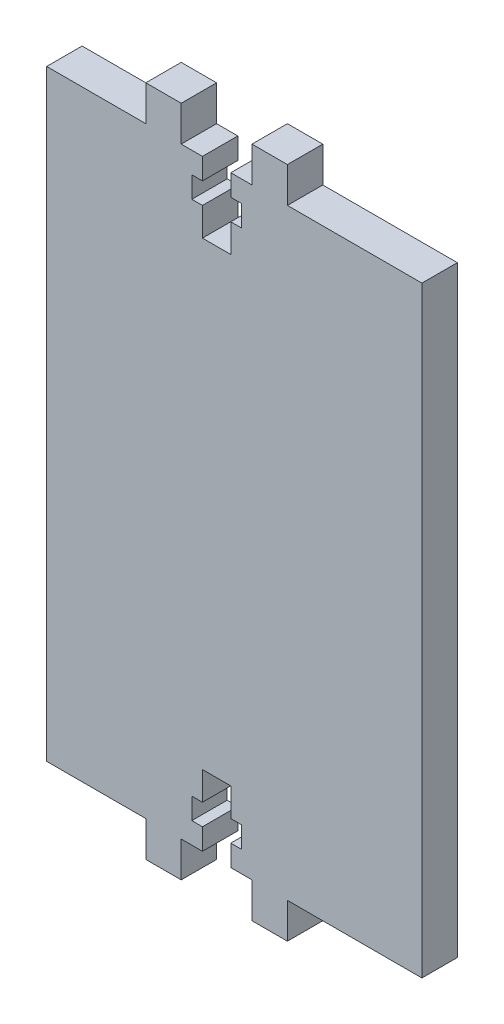
SolidWorks part; units mm, degrees
ref_plane "Plan de face" through (0, 0, 0) normal (0, 0, 1) x (1, 0, 0)
ref_plane "Plan de dessus" through (0, 0, 0) normal (0, 1, 0) x (1, 0, 0)
ref_plane "Plan de droite" through (0, 0, 0) normal (1, 0, 0) x (0, 0, -1)
sketch "Esquisse2" plane through (0, 0, 0) normal (0, 0, 1) x (1, 0, 0)
  line L0 (-10, 0) -> (-24, 0)
  line L1 (-24, 0) -> (-24, 85)
  line L2 (-24, 85) -> (29, 85) construction
  line L3 (29, 85) -> (29, 0)
  line L4 (29, 0) -> (10, 0)
  line L5 (0, 0) -> (0, 85) construction
  line L6 (-23.359, 42.5) -> (29, 42.5) construction
  line L7 (-10, 85) -> (-24, 85)
  line L8 (29, 85) -> (10, 85)
  line B0 (-3.5, 3) -> (-3.5, 6)
  line B1 (2, 6) -> (2, 10)
  line B2 (-2, 10) -> (-2, 6)
  line B3 (-3.5, 6) -> (-2, 6)
  line B4 (0, 0) -> (0, 11.2208) construction
  line B5 (-2, 0) -> (-5, 0)
  line B6 (-5, -5) -> (-10, -5)
  line B7 (-10, -5) -> (-10, 0)
  line B8 (-5, -5) -> (-5, 0)
  line B9 (2, 0) -> (5, 0)
  line B10 (5, 0) -> (5, -5)
  line B11 (5, -5) -> (10, -5)
  line B12 (10, -5) -> (10, 0)
  line B13 (-2, 0) -> (2, 0) construction
  line B14 (2, 0) -> (2, 3)
  line B15 (2, 6) -> (3.5, 6)
  line B16 (3.5, 3) -> (2, 3)
  line B17 (2, 10) -> (-2, 10)
  line B18 (-2, 3) -> (-3.5, 3)
  line B19 (3.5, 6) -> (3.5, 3)
  line B20 (-2, 3) -> (-2, 0)
  line B21 (0, 10) -> (0, 0) construction
  line B22 (-3.5, 82) -> (-3.5, 79)
  line B23 (2, 79) -> (2, 75)
  line B24 (-2, 75) -> (-2, 79)
  line B25 (-3.5, 79) -> (-2, 79)
  line B26 (0, 85) -> (0, 73.7792) construction
  line B27 (-2, 85) -> (-5, 85)
  line B28 (-5, 90) -> (-10, 90)
  line B29 (-10, 90) -> (-10, 85)
  line B30 (-5, 90) -> (-5, 85)
  line B31 (2, 85) -> (5, 85)
  line B32 (5, 85) -> (5, 90)
  line B33 (5, 90) -> (10, 90)
  line B34 (10, 90) -> (10, 85)
  line B35 (-2, 85) -> (2, 85) construction
  line B36 (2, 85) -> (2, 82)
  line B37 (2, 79) -> (3.5, 79)
  line B38 (3.5, 82) -> (2, 82)
  line B39 (2, 75) -> (-2, 75)
  line B40 (-2, 82) -> (-3.5, 82)
  line B41 (3.5, 79) -> (3.5, 82)
  line B42 (-2, 82) -> (-2, 85)
  line B43 (0, 75) -> (0, 85) construction
  dimension "D1" = 24
  dimension "D2" = 29
  dimension "D3" = 85
sketch_block_instance "Insert M4 plots ep 5mm-1"
sketch_block "Insert M4 plots ep 5mm" parameters "D1"=10, "D2"=5, "D3"=5, "D4"=7, "D5"=4, "D6"=3, "D7"=3, "D8"=10
sketch_block_instance "Insert M4 plots ep 5mm-3"
extrude "Boss.-Extru.1" add sketch "Esquisse2" along normal blind 5 contours B40 B42 B27 B30 B28 B29 L7 L1 L0 B7 B6 B8 B5 B20 B18 B0 B3 B2 B17 B1 B15 B19 B16 B14 B9 B10 B11 B12 L4 L3 L8 B34 B33 B32 B31 B36 B38 B41 B37 B23 B39 B24 B25 B22
